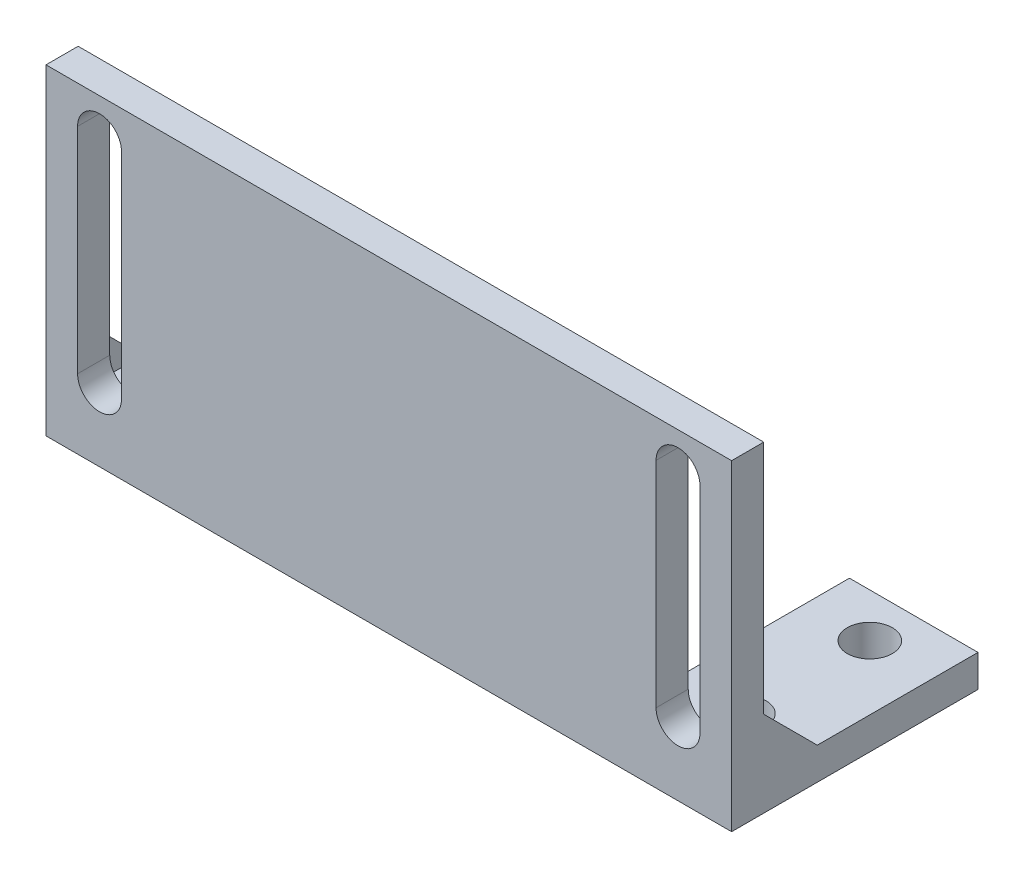
SolidWorks part; units mm, degrees
ref_plane "Front Plane" through (0, 0, 0) normal (0, 0, 1) x (1, 0, 0)
ref_plane "Top Plane" through (0, 0, 0) normal (0, 1, 0) x (1, 0, 0)
ref_plane "Right Plane" through (0, 0, 0) normal (1, 0, 0) x (0, 0, -1)
sketch "Sketch1" plane through (0, 0, 0) normal (0, 1, 0) x (1, 0, 0)
  line L0 (0, 0) -> (0, 23)
  line L1 (0, 23) -> (12, 23)
  line L2 (12, 23) -> (12, 3)
  line L3 (12, 3) -> (52, 3)
  line L4 (52, 3) -> (52, 23)
  line L5 (52, 23) -> (64, 23)
  line L6 (64, 23) -> (64, 0)
  line L7 (64, 0) -> (0, 0)
  dimension "D1" = 23
  dimension "D2" = 12
  dimension "D3" = 40
  dimension "D4" = 12
  dimension "D5" = 23
  dimension "D6" = 20
  dimension "D7" = 20
extrude "Boss-Extrude1" add sketch "Sketch1" against normal blind 3
sketch "Sketch2" plane through (0, -3, 0) normal (0, -1, 0) x (-1, 0, 0)
  line L1 (-12, 23) -> (0, 23) construction
  line L4 (-12, 3) -> (-12, 23) construction
  line L5 (-32, -997) -> (-32, 49003) construction
  line L6 (-52, 3) -> (-12, 3) construction
  circle A0 centre (-6, 18.9) radius 2.1
  circle A1 centre (-6, 7.1) radius 2.1
  circle A4 centre (-58, 7.1) radius 2.1
  circle A5 centre (-58, 18.9) radius 2.1
  point P13 (-32, 3)
  dimension "D2" = 4.2
  dimension "D3" = 4.2
  dimension "D1" = 4.1
  dimension "D4" = 11.8
  dimension "D5" = 6
  dimension "D6" = 6
extrude "Cut-Extrude1" cut sketch "Sketch2" against normal blind 3
sketch "Sketch3" plane through (0, 0, 0) normal (0, 1, 0) x (1, 0, 0)
  line L0 (12, 3) -> (0, 3)
  line L1 (0, 23) -> (0, 0) construction
  line L2 (52, 3) -> (64, 3)
  line L3 (64, 0) -> (64, 23) construction
  line M5 (0, 0) -> (64, 0)
  line M6 (64, 0) -> (64, 23)
  line M9 (52, 3) -> (12, 3)
  line M12 (0, 23) -> (0, 0)
extrude "Boss-Extrude2" add sketch "Sketch3" along normal blind 27 contours L2 L0 M9 M12 M5 M6
sketch "Sketch4" plane through (0, 0, -3) normal (0, 0, -1) x (-1, 0, 0)
  line L0 (-59, 23.5) -> (-59, 3.5) construction
  line L1 (-56.95, 23.5) -> (-56.95, 3.5)
  line L2 (-61.05, 23.5) -> (-61.05, 3.5)
  line L3 (-64, 27) -> (-64, 0) construction
  line L4 (0, 27) -> (-64, 27) construction
  line L6 (-32, -973) -> (-32, 49027) construction
  line L7 (-5, 23.5) -> (-5, 3.5) construction
  line L8 (-7.05, 23.5) -> (-7.05, 3.5)
  line L9 (-2.95, 23.5) -> (-2.95, 3.5)
  arc A0 (-56.95, 23.5) -> (-61.05, 23.5) centre (-59, 23.5) ccw
  arc A1 (-61.05, 3.5) -> (-56.95, 3.5) centre (-59, 3.5) ccw
  arc A2 (-7.05, 23.5) -> (-2.95, 23.5) centre (-5, 23.5) cw
  arc A3 (-2.95, 3.5) -> (-7.05, 3.5) centre (-5, 3.5) cw
  point P2 (-59, 13.5)
  point P14 (-32, 27)
  point P16 (-5, 13.5)
  dimension "D2" = 2.05
  dimension "D1" = 5
  dimension "D3" = 3.5
  dimension "D4" = 20
extrude "Cut-Extrude2" cut sketch "Sketch4" against normal blind 27
ref_plane "Plane1" through (64, 0, 0) normal (1, 0, 0) x (0, 0, -1)
sketch "Sketch5" plane through (64, 0, 0) normal (1, 0, 0) x (0, 0, -1)
  line L0 (3, 5) -> (8, 0)
  line L1 (3, 27) -> (3, 0) construction
  line L2 (3, 0) -> (23, 0) construction
  dimension "D1" = 5
  dimension "D2" = 5
rib "Rib1" sketch "Sketch5" sketch "Sketch5" thickness 1 extrusion direction parallel to sketch draft on no parameters "D1"=1
sketch "Sketch6" plane through (0, 0, 0) normal (1, 0, 0) x (0, 0, -1)
  line L0 (3, 5) -> (8, 0)
rib "Rib2" sketch "Sketch6" sketch "Sketch6" thickness 1 parameters "D1"=1
